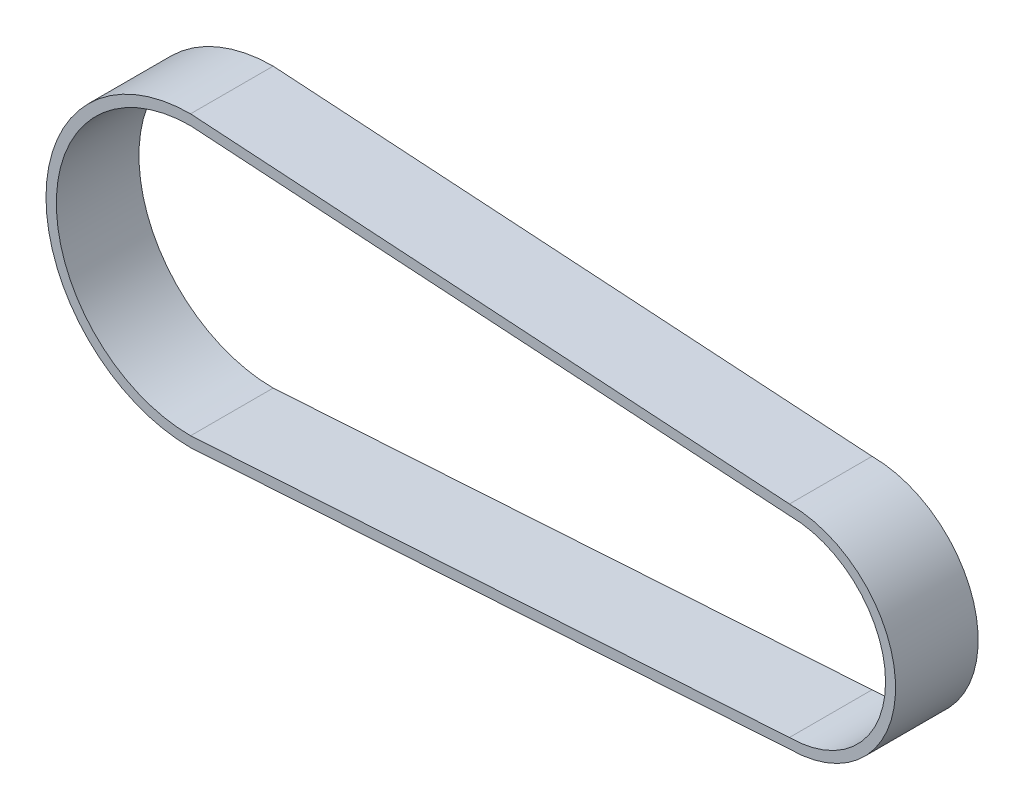
SolidWorks part; units mm, degrees
ref_plane "Plan de face" through (0, 0, 0) normal (0, 0, 1) x (1, 0, 0)
ref_plane "Plan de dessus" through (0, 0, 0) normal (0, 1, 0) x (1, 0, 0)
ref_plane "Plan de droite" through (0, 0, 0) normal (1, 0, 0) x (0, 0, -1)
sketch "Esquisse1" plane through (0, 0, 0) normal (0, 0, 1) x (1, 0, 0)
  line L0 (0, 0) -> (25, 0) construction
  line L1 (0, 0) -> (-33, 0) construction
  line L2 (-33, -13) -> (25, -9.3058)
  line L3 (25, 9.3058) -> (-33, 13)
  line L4 (-33, -14) -> (25, -10.2761)
  line L5 (25, 10.2761) -> (-33, 14)
  circle A0 centre (-33, 0) radius 13 construction
  circle A1 centre (25, 0) radius 9.3058 construction
  circle A2 centre (25, 0) radius 10.2761 construction
  circle A3 centre (-33, 0) radius 14 construction
  arc A4 (-33, 14) -> (-33, -14) centre (-33, 0) ccw
  arc A5 (-33, 13) -> (-33, -13) centre (-33, 0) ccw
  arc A6 (25, 9.3058) -> (25, -9.3058) centre (25, 0) cw
  arc A7 (25, -10.2761) -> (25, 10.2761) centre (25, 0) ccw
extrude "Boss.-Extru.1" add sketch "Esquisse1" along normal blind 8
